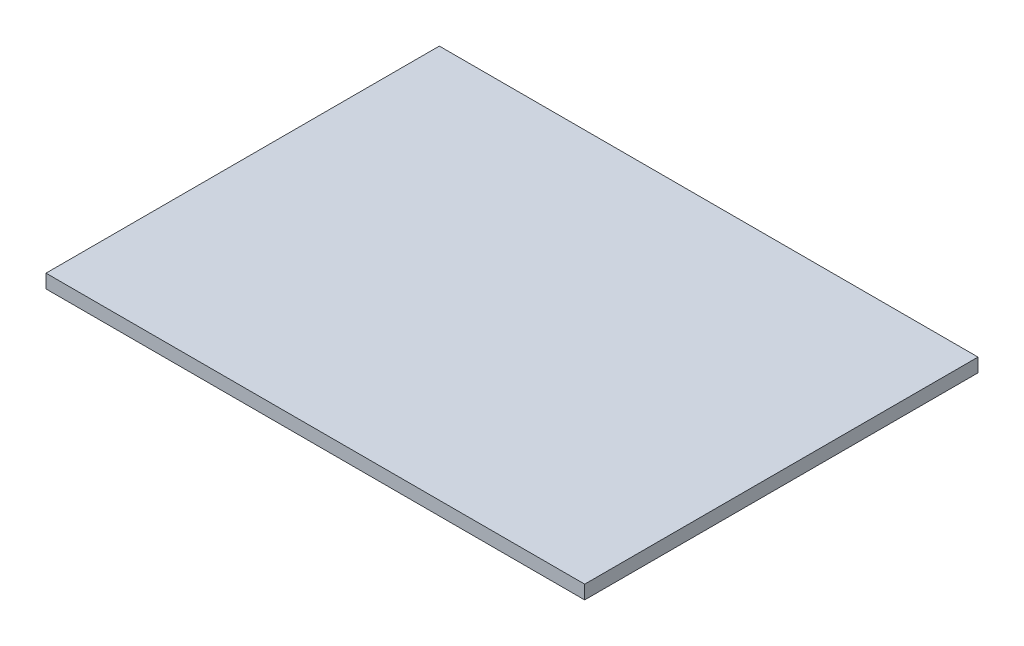
SolidWorks part; units mm, degrees
ref_plane "Front Plane" through (0, 0, 0) normal (0, 0, 1) x (1, 0, 0)
ref_plane "Top Plane" through (0, 0, 0) normal (0, 1, 0) x (1, 0, 0)
ref_plane "Right Plane" through (0, 0, 0) normal (1, 0, 0) x (0, 0, -1)
sketch "Sketch1" plane through (0, 0, 0) normal (0, 1, 0) x (1, 0, 0)
  line L1 (0, 0) -> (63, 0)
  line L2 (0, 0) -> (0, 46)
  line L3 (0, 46) -> (63, 46)
  line L4 (63, 0) -> (63, 46)
  dimension "D1" = 63
  dimension "D2" = 46
extrude "Boss-Extrude1" add sketch "Sketch1" along normal blind 1.6
